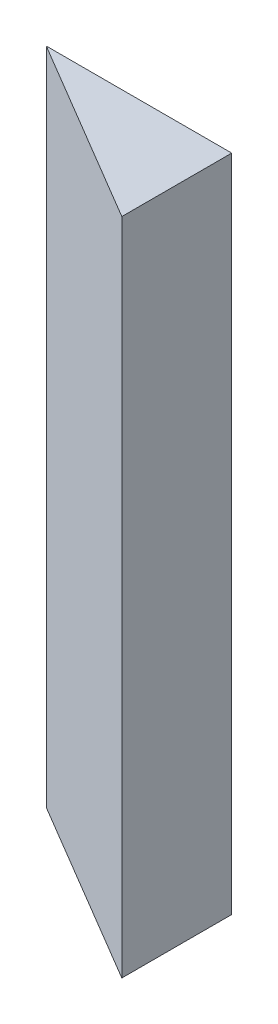
SolidWorks part; units mm, degrees
ref_plane "Front Plane" through (0, 0, 0) normal (0, 0, 1) x (1, 0, 0)
ref_plane "Top Plane" through (0, 0, 0) normal (0, 1, 0) x (1, 0, 0)
ref_plane "Right Plane" through (0, 0, 0) normal (1, 0, 0) x (0, 0, -1)
sketch "Sketch1" plane through (0, 0, 0) normal (0, 1, 0) x (1, 0, 0)
  line L0 (0, 0) -> (0, -16.9333)
  line L1 (0, -16.9333) -> (-28.575, 0)
  line L2 (-28.575, 0) -> (0, 0)
  dimension "D1" = 28.575
  dimension "D2" = 16.9333
extrude "Boss-Extrude1" add sketch "Sketch1" along normal mid plane 101.6
